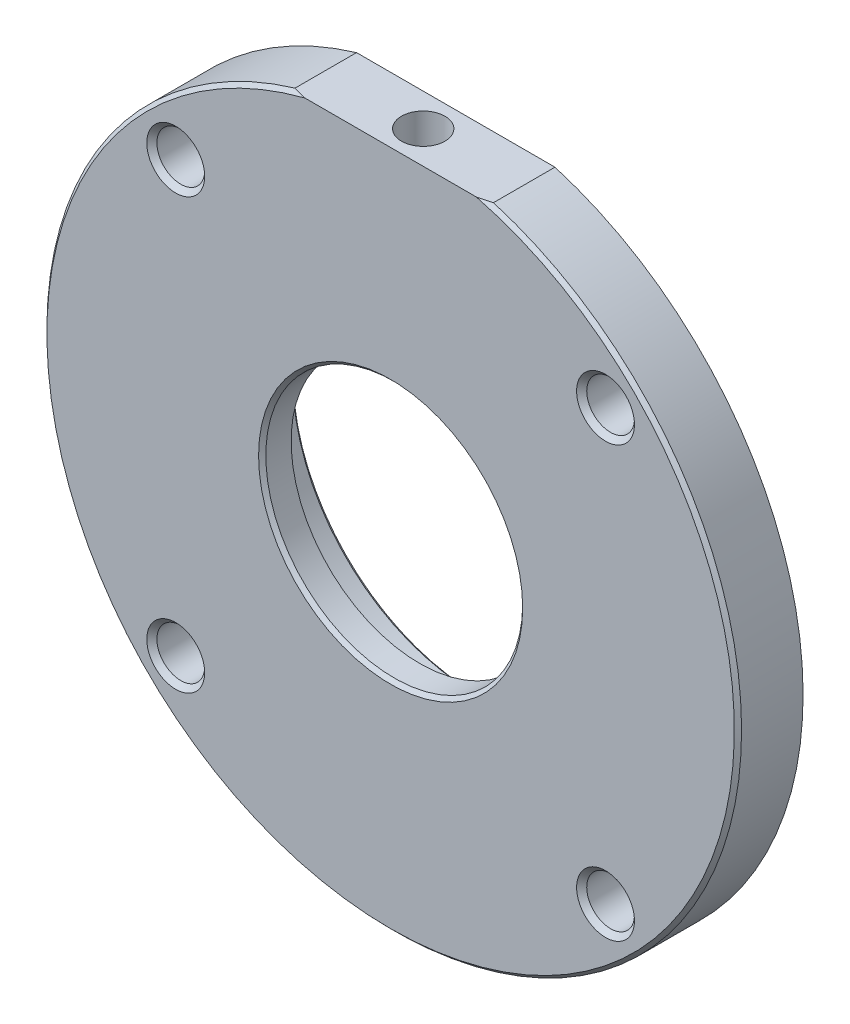
SolidWorks part; units mm, degrees
material "Nickel"
ref_plane "Front Plane" through (0, 0, 0) normal (0, 0, 1) x (1, 0, 0)
ref_plane "Top Plane" through (0, 0, 0) normal (0, 1, 0) x (1, 0, 0)
ref_plane "Right Plane" through (0, 0, 0) normal (1, 0, 0) x (0, 0, -1)
sketch "Sketch1" plane through (0, 0, 0) normal (1, 0, 0) x (0, 0, -1)
  line L0 (0, 0) -> (83.4983, 0) construction
  line L1 (0, -18.25) -> (0, -47.5)
  line L2 (0.5, -48) -> (9, -48)
  line L3 (9, -48) -> (9, -36)
  line L4 (9, -36) -> (13.5, -36)
  line L5 (14, -35.5) -> (14, -30)
  line L6 (14, -30) -> (12, -30)
  line L7 (12, -30) -> (12, -25.5)
  line L8 (11.5, -25) -> (4, -25)
  line L9 (4, -25) -> (4, -17.75)
  line L10 (4, -17.75) -> (0.5, -17.75)
  line L11 (0, -47.5) -> (0.5, -48)
  line L12 (13.5, -36) -> (14, -35.5)
  line L13 (12, -25.5) -> (11.5, -25)
  line L14 (0.5, -17.75) -> (0, -18.25)
  point P3 (0, -17.75)
  point P4 (0, -48)
  point P8 (14, -36)
  point P11 (12, -25)
  dimension "D1" = 35.5
  dimension "D2" = 50
  dimension "D3" = 60
  dimension "D4" = 72
  dimension "D5" = 96
  dimension "D6" = 0.5
  dimension "D7" = 45
  dimension "D8" = 0.5
  dimension "D9" = 45
  dimension "D10" = 0.5
  dimension "D11" = 45
  dimension "D12" = 0.5
  dimension "D13" = 45
  dimension "D14" = 14
  dimension "D15" = 2
  dimension "D16" = 10
  dimension "D17" = 5
revolve "Revolve1" add sketch "Sketch1" angle 360 about L0
hole_wizard "Ø6.0mm Dowel Hole1" positions "Sketch2" profile "Sketch3" hole size "Ø6.0" standard "ANSI Metric" end condition up to next
sketch "Sketch2" plane through (0, 0, -9) normal (0, 0, -1) x (-1, 0, 0)
  line L0 (29.6985, 29.6985) -> (0, 0) construction
  line L2 (0, 0) -> (0, 44.7702) construction
  point P0 (29.6985, 29.6985)
  dimension "D1" = 45
  dimension "D2" = 42
sketch "Sketch3" plane through (-29.6985, 29.6985, -9) normal (1, 0, 0) x (0, 1, 0)
  line L0 (0, 0) -> (0, 9)
  line L1 (0, 9) -> (4, 9)
  line L2 (3.3, 8.3) -> (3.3, 0.7)
  line L3 (3.3, 0.7) -> (4, 0)
  line L5 (4, 0) -> (0, 0)
  line L6 (-3.3, 0.7) -> (-4, 0) construction
  line L7 (4, 9) -> (3.3, 8.3)
  line L8 (-4, 9) -> (-3.3, 8.3) construction
  line L11 (0, -6.35) -> (0, 107.95) construction
  dimension "Thru Hole Dia." = 6.6
  dimension "Thru Hole Depth" = 9
  dimension "Near C'Sink Dia." = 8
  dimension "Near C'Sink Angle" = 90
  dimension "Far C'Sink Dia." = 8
  dimension "Far C'Sink Angle" = 90
pattern_circular "CirPattern1" count 4 over 360 about axis through (0, 0, 0) along (0, 0, 1) of "Ø6.0mm Dowel Hole1"
sketch "Sketch4" plane through (0, 0, -9) normal (0, 0, -1) x (-1, 0, 0)
  line L1 (-47.1255, 66.6649) -> (46.7278, 66.6649)
  line L2 (-47.1255, 66.6649) -> (-47.1255, 46)
  line L3 (-47.1255, 46) -> (46.7278, 46)
  line L4 (46.7278, 66.6649) -> (46.7278, 46)
  dimension "D1" = 46
extrude "Cut-Extrude1" cut sketch "Sketch4" against normal through all
hole_wizard "Ø3.0mm Dowel Hole1" positions "Sketch5" profile "Sketch6" hole size "Ø3.0" standard "ANSI Metric"
sketch "Sketch5" plane through (0, 0, -12) normal (0, 0, -1) x (-1, 0, 0)
  line L0 (-13.7113, 46) -> (13.7113, 46) construction
  point P0 (0, 28)
  point P5 (0, 0)
  dimension "D1" = 18
sketch "Sketch6" plane through (0, 28, -12) normal (1, 0, 0) x (0, 1, 0)
  line L0 (0, 0) -> (0, 10)
  line L1 (0, 10) -> (1.5, 9.0987)
  line L2 (1.5, 9.0987) -> (1.5, 0.25)
  line L3 (1.5, 0.25) -> (1.75, 0)
  line L5 (1.75, 0) -> (0, 0)
  line L6 (-1.5, 0.25) -> (-1.75, 0) construction
  line L10 (0, 10) -> (-1.5, 9.0987) construction
  line L11 (0, -6.35) -> (0, 107.95) construction
  dimension "Hole Dia." = 3
  dimension "Hole Depth" = 10
  dimension "Near C'Sink Dia." = 3.5
  dimension "Near C'Sink Angle" = 90
  dimension "Drill Angle" = 118
hole_wizard "Hole1" positions "Sketch8" profile "Sketch9" legacy
sketch "Sketch8" plane through (0, 46, 0) normal (0, 1, 0) x (1, 0, 0)
  line L0 (-11.8427, 0) -> (11.8427, 0) construction
  point P0 (0, 4.5)
  dimension "D1" = 4.5
sketch "Sketch9" plane through (0, 46, -4.5) normal (1, 0, 0) x (0, 0, 1)
  line L0 (0, 0) -> (0, 18)
  line L1 (0, 18) -> (1.5, 17.0987)
  line L2 (1.5, 17.0987) -> (1.5, 7.9013)
  line L3 (1.5, 7.9013) -> (3, 7)
  line L4 (3, 7) -> (3, 0)
  line L5 (3, 0) -> (0, 0)
  line L6 (0, -6.13) -> (0, 109.2824) construction
  line L7 (-1.5, 7.9013) -> (-3, 7) construction
  line L8 (0, 18) -> (-1.5, 17.0987) construction
  dimension "Diameter" = 3
  dimension "Depth" = 18
  dimension "C-Drill Diameter" = 6
  dimension "C-Drill Depth" = 7
  dimension "Drill Angle" = 118
  dimension "C-Drill Angle" = 118
